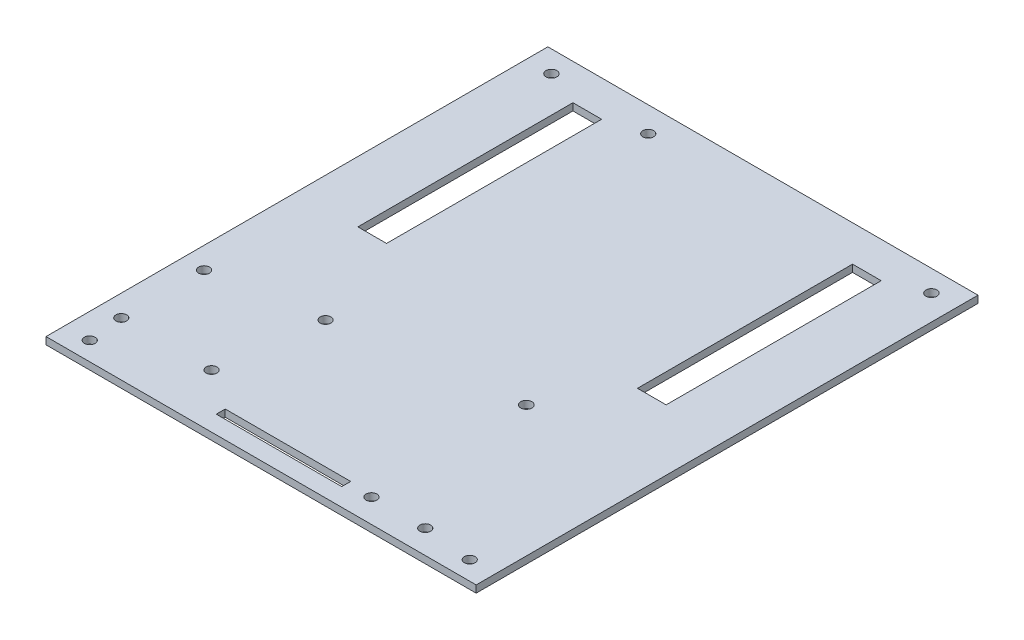
SolidWorks part; units mm, degrees
material "Perspex (TM) GS Acrylic Cast Sheet"
ref_plane "Front Plane" through (0, 0, 0) normal (0, 0, 1) x (1, 0, 0)
ref_plane "Top Plane" through (0, 0, 0) normal (0, 1, 0) x (1, 0, 0)
ref_plane "Right Plane" through (0, 0, 0) normal (1, 0, 0) x (0, 0, -1)
sketch "Sketch1" plane through (0, 0, 0) normal (0, 1, 0) x (1, 0, 0)
  line L1 (60, -70) -> (-60, -70)
  line L2 (60, -70) -> (60, 70)
  line L3 (60, 70) -> (-60, 70)
  line L4 (-60, -70) -> (-60, 70)
  line L5 (60, -70) -> (-60, 70) construction
  line L6 (60, 70) -> (-60, -70) construction
  point P0 (0, 0)
  dimension "D1" = 140
  dimension "D2" = 120
extrude "Boss-Extrude1" add sketch "Sketch1" along normal blind 2
sketch "Sketch2" plane through (0, 2, 0) normal (0, 1, 0) x (1, 0, 0)
  line L0 (0, 0) -> (0, 70) construction
  line L1 (60, 70) -> (-60, 70) construction
  line L2 (0, 0) -> (-60, 0) construction
  line L3 (-60, 70) -> (-60, -70) construction
  line L4 (-60, -70) -> (60, -70) construction
  circle A0 centre (-53, 64) radius 1.525
  circle A1 centre (-53, -64.8) radius 1.5
  circle A2 centre (53, 64) radius 1.525
  circle A3 centre (53, -64.8) radius 1.5
  dimension "D1" = 3.05
  dimension "D2" = 6
  dimension "D3" = 7
  dimension "D4" = 3
  dimension "D5" = 5.2
  dimension "D6" = 7
extrude "Cut-Extrude1" cut sketch "Sketch2" against normal blind 2
sketch "Sketch4" plane through (0, 2, 0) normal (0, 1, 0) x (1, 0, 0)
  line L0 (60, 70) -> (-60, 70) construction
  line L1 (-60, 70) -> (-60, -70) construction
  line L2 (0, 0) -> (0, 70) construction
  line L3 (-35, 60) -> (-43, 60)
  line L4 (-35, 60) -> (-35, 0)
  line L5 (-35, 0) -> (-43, 0)
  line L6 (-43, 60) -> (-43, 0)
  line L7 (-35, 60) -> (-43, 0) construction
  line L8 (-35, 0) -> (-43, 60) construction
  line L9 (35, 0) -> (43, 0)
  line L10 (35, 60) -> (35, 0)
  line L11 (43, 60) -> (43, 0)
  line L12 (35, 60) -> (43, 60)
  line L13 (60, -70) -> (60, 70) construction
  circle A0 centre (-25, 63) radius 1.5
  circle A1 centre (-25, -27) radius 1.5
  circle A2 centre (23.5, -19.5) radius 1.55
  point P10 (-39, 30)
  dimension "D1" = 3
  dimension "D2" = 3
  dimension "D4" = 7
  dimension "D5" = 35
  dimension "D6" = 35
  dimension "D7" = 3.1
  dimension "D8" = 36.5
  dimension "D3" = 90
  dimension "78" = 89.5
  dimension "D10" = 8
  dimension "D11" = 10
  dimension "D12" = 60
  dimension "D13" = 17
extrude "Cut-Extrude2" cut sketch "Sketch4" against normal through all
sketch "Sketch5" plane through (0, 2, 0) normal (0, 1, 0) x (1, 0, 0)
  line L0 (-60, 70) -> (-60, -70) construction
  line L1 (-60, -70) -> (60, -70) construction
  line L3 (17.5, -65) -> (-17.5, -65)
  line L4 (17.5, -65) -> (17.5, -62.5)
  line L5 (17.5, -62.5) -> (-17.5, -62.5)
  line L6 (-17.5, -65) -> (-17.5, -62.5)
  line L7 (17.5, -65) -> (-17.5, -62.5) construction
  line L8 (17.5, -62.5) -> (-17.5, -65) construction
  circle A0 centre (-54, -55) radius 1.5
  circle A1 centre (-28.82, -55) radius 1.5
  circle A2 centre (-54, -31.9) radius 1.5
  circle A3 centre (24.1836, -63.3826) radius 1.5
  circle A4 centre (39.1836, -63.3826) radius 1.5
  point P10 (0, -63.75)
  dimension "D1" = 3
  dimension "D2" = 3
  dimension "D4" = 3
  dimension "D8" = 15
  dimension "D9" = 15
  dimension "D3" = 25.18
  dimension "D5" = 23.1
  dimension "D6" = 6
  dimension "D7" = 6
  dimension "D10" = 5
  dimension "D11" = 2.5
  dimension "D12" = 35
  dimension "D13" = 0
extrude "Cut-Extrude3" cut sketch "Sketch5" against normal through all
